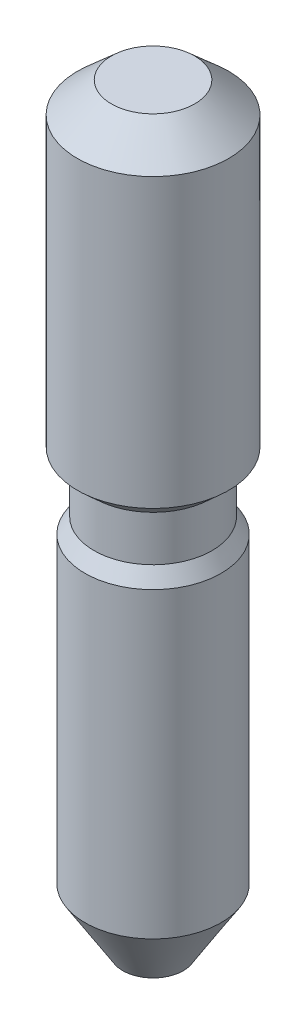
SolidWorks part; units mm, degrees
ref_plane "Alzado" through (0, 0, 0) normal (0, 0, 1) x (1, 0, 0)
ref_plane "Planta" through (0, 0, 0) normal (0, 1, 0) x (1, 0, 0)
ref_plane "Vista lateral" through (0, 0, 0) normal (1, 0, 0) x (0, 0, -1)
sketch "Sketch1" plane through (0, 0, 0) normal (0, 0, 1) x (1, 0, 0)
  line L0 (0, 0) -> (2.75, 0)
  line L1 (2.75, 0) -> (5, -2)
  line L2 (5, -2) -> (5, -21)
  line L3 (5, -21) -> (3.9, -22)
  line L4 (3.9, -22) -> (3.9, -25)
  line L5 (3.9, -25) -> (4.5, -26)
  line L6 (4.5, -26) -> (4.5, -46)
  line L7 (4.5, -46) -> (2, -50)
  line L8 (2, -50) -> (0, -50)
  line L9 (0, -50) -> (0, 0)
  line L10 (0, -54) -> (0, 4) construction
revolve "Motor_reductora_husillo" add sketch "Sketch1" angle 360 about L10
